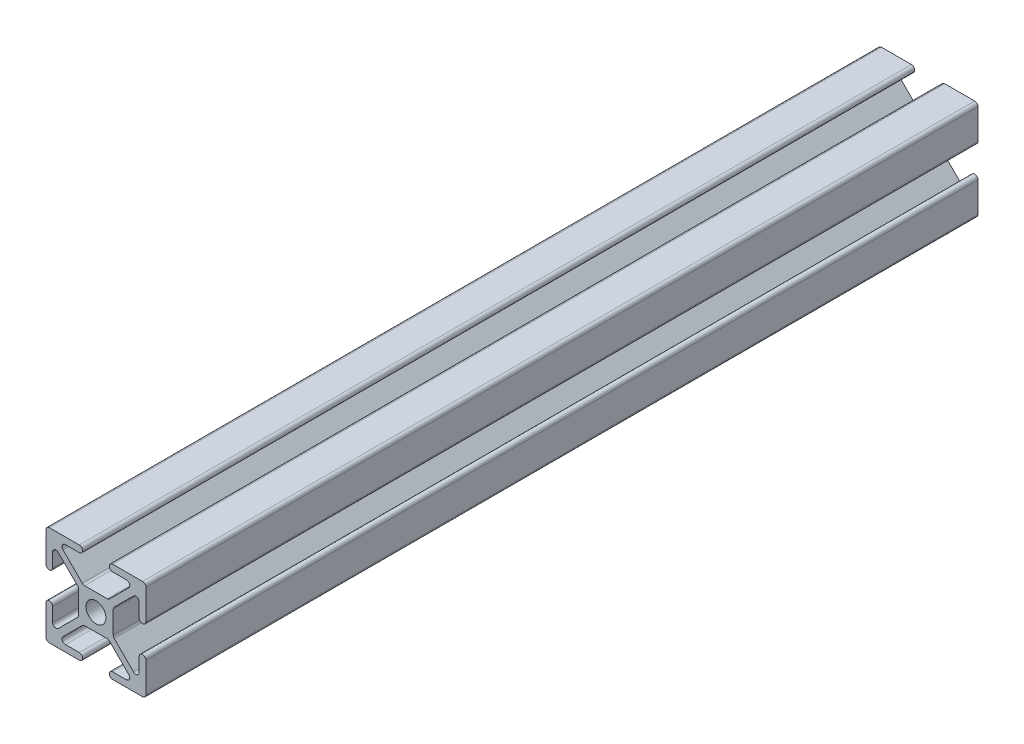
SolidWorks part; units mm, degrees
ref_plane "Alzado" through (0, 0, 0) normal (0, 0, 1) x (1, 0, 0)
ref_plane "Planta" through (0, 0, 0) normal (0, 1, 0) x (1, 0, 0)
ref_plane "Vista lateral" through (0, 0, 0) normal (1, 0, 0) x (0, 0, -1)
sketch "Croquis1" plane through (0, 0, 0) normal (0, 0, 1) x (1, 0, 0)
  line L1 (-14, 15) -> (14, 15)
  line L2 (-15, 14) -> (-15, -14)
  line L3 (-14, -15) -> (14, -15)
  line L4 (15, 14) -> (15, -14)
  line L5 (-15, 15) -> (15, -15) construction
  line L6 (-15, -15) -> (15, 15) construction
  arc A0 (-14, 15) -> (-15, 14) centre (-14, 14) ccw
  arc A1 (14, -15) -> (15, -14) centre (14, -14) ccw
  arc A2 (-14, -15) -> (-15, -14) centre (-14, -14) cw
  arc A3 (15, 14) -> (14, 15) centre (14, 14) ccw
  point P0 (0, 0)
  dimension "D3" = 1
  dimension "D4" = 1
  dimension "D1" = 30
  dimension "D2" = 30
extrude "Saliente-Extruir1" add sketch "Croquis1" against normal blind 1400
sketch "Croquis2" plane through (0, 0, 0) normal (0, 0, 1) x (1, 0, 0)
  circle A0 centre (0, 0) radius 3
  dimension "D1" = 6
sketch "Croquis3" plane through (0, 0, 0) normal (0, 0, 1) x (1, 0, 0)
  line L0 (-15, 0) -> (15, 0) construction
  line L1 (4.0787, -5.4929) -> (9.8787, -11.2929)
  line L2 (-11.2929, 9.8787) -> (-5.4929, 4.0787)
  line L3 (-9.8787, 11.2929) -> (-4.0787, 5.4929)
  line L4 (-13, 9.1716) -> (-13, 5)
  line L5 (-15, 14) -> (-15, -14) construction
  line L6 (-5.2, 3.3716) -> (-5.2, -3.3716)
  line L7 (-9.1716, 13) -> (-5, 13)
  line L8 (9.8787, 11.2929) -> (4.0787, 5.4929)
  line L9 (11.2929, 9.8787) -> (5.4929, 4.0787)
  line L10 (-3.3716, 5.2) -> (3.3716, 5.2)
  line L11 (14, 15) -> (-14, 15) construction
  line L12 (13, 9.1716) -> (13, 5)
  line L13 (5.2, 3.3716) -> (5.2, -3.3716)
  line L14 (15, -14) -> (15, 14) construction
  line L15 (-9.1716, -13) -> (-5, -13)
  line L16 (-3.3716, -5.2) -> (3.3716, -5.2)
  line L17 (-14, -15) -> (14, -15) construction
  line L18 (-5.4929, -4.0787) -> (-11.2929, -9.8787)
  line L19 (5.4929, -4.0787) -> (11.2929, -9.8787)
  line L20 (-4.0787, -5.4929) -> (-9.8787, -11.2929)
  line L21 (5, -13) -> (9.1716, -13)
  line L22 (-13, -5) -> (-13, -9.1716)
  line L23 (13, -5) -> (13, -9.1716)
  line L24 (0, 15) -> (0, -5.2) construction
  line L34 (5, 13) -> (9.1716, 13)
  arc A0 (9.8787, 11.2929) -> (9.1716, 13) centre (9.1716, 12) ccw
  arc A1 (-9.8787, 11.2929) -> (-9.1716, 13) centre (-9.1716, 12) cw
  arc A2 (9.8787, 11.2929) -> (9.1716, 13) centre (9.1716, 12) ccw
  arc A3 (13, 9.1716) -> (11.2929, 9.8787) centre (12, 9.1716) ccw
  arc A4 (11.2929, -9.8787) -> (13, -9.1716) centre (12, -9.1716) ccw
  arc A5 (9.1716, -13) -> (9.8787, -11.2929) centre (9.1716, -12) ccw
  arc A6 (-9.1716, -13) -> (-9.8787, -11.2929) centre (-9.1716, -12) cw
  arc A7 (-11.2929, -9.8787) -> (-13, -9.1716) centre (-12, -9.1716) cw
  arc A8 (-13, 9.1716) -> (-11.2929, 9.8787) centre (-12, 9.1716) cw
  arc A9 (-4.0787, -5.4929) -> (-3.3716, -5.2) centre (-3.3716, -6.2) cw
  arc A10 (3.3716, -5.2) -> (4.0787, -5.4929) centre (3.3716, -6.2) cw
  arc A11 (5.4929, -4.0787) -> (5.2, -3.3716) centre (6.2, -3.3716) cw
  arc A12 (5.2, 3.3716) -> (5.4929, 4.0787) centre (6.2, 3.3716) cw
  arc A13 (3.3716, 5.2) -> (4.0787, 5.4929) centre (3.3716, 6.2) ccw
  arc A14 (-3.3716, 5.2) -> (-4.0787, 5.4929) centre (-3.3716, 6.2) cw
  arc A15 (-5.4929, -4.0787) -> (-5.2, -3.3716) centre (-6.2, -3.3716) ccw
  arc A16 (-5.2, 3.3716) -> (-5.4929, 4.0787) centre (-6.2, 3.3716) ccw
  circle A17 centre (-14, -5) radius 1
  circle A18 centre (-14, 5) radius 1
  circle A19 centre (-5, -14) radius 1
  circle A20 centre (5, -14) radius 1
  circle A21 centre (14, 5) radius 1
  circle A22 centre (14, -5) radius 1
  circle A23 centre (-5, 14) radius 1
  circle A24 centre (5, 14) radius 1
  point P20 (-11.5858, -13)
  point P30 (-13, -11.5858)
  point P43 (-3.7858, -5.2)
  point P50 (3.7858, -5.2)
  point P53 (5.2, -3.7858)
  point P62 (-5.2, -3.7858)
  line M2 (-15, 14) -> (-15, -14)
  line M4 (-14, -15) -> (14, -15)
  line M6 (15, -14) -> (15, 14)
  line M8 (14, 15) -> (-14, 15)
  dimension "D6" = 9.8
  dimension "D7" = 2
  dimension "D12" = 2
  dimension "D19" = 1
  dimension "D2" = 1
  dimension "D3" = 1
  dimension "D4" = 1
  dimension "D16" = 1
  dimension "D5" = 2
  dimension "D8" = 9.8
  dimension "D9" = 2
  dimension "D10" = 9.8
  dimension "D11" = 9.8
  dimension "D15" = 1
  dimension "D20" = 1
  dimension "D23" = 1
  dimension "D24" = 1
  dimension "D27" = 1
  dimension "D28" = 1
extrude "Cortar-Extruir1" cut sketch "Croquis2" against normal through all
extrude "Cortar-Extruir3" cut sketch "Croquis3" against normal through all contours A18 A17 L22 A7 L18 A15 L6 A16 L2 A8 L4 M2 | A24 A23 L7 A1 L3 A14 L10 A13 L8 A0 L34 M8 | A20 L21 A5 L1 A10 L16 A9 L20 A6 L15 A19 M4 | A22 A21 L12 A3 L9 A12 L13 A11 L19 A4 L23 M6
sketch "Croquis4" plane through (-15, 0, 0) normal (-1, 0, 0) x (0, 0, 1)
  line L0 (0, 14) -> (0, 5) construction
  line L1 (-1400, 15) -> (-250, 15)
  line L2 (-1400, 15) -> (-1400, -57.7484)
  line L3 (-1400, -57.7484) -> (-250, -57.7484)
  line L4 (-250, 15) -> (-250, -57.7484)
  dimension "D1" = 250
extrude "Cortar-Extruir5" cut sketch "Croquis4" against normal blind 254
